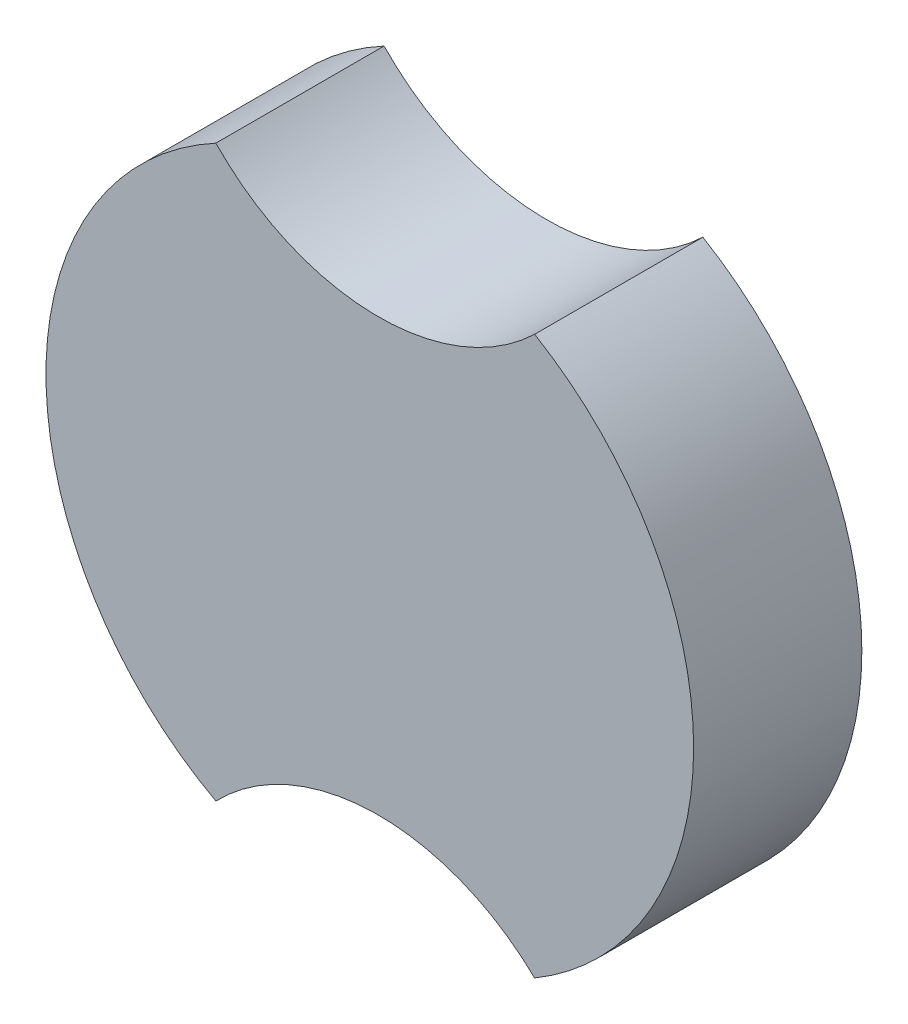
SolidWorks part; units mm, degrees
ref_plane "Спереди" through (0, 0, 0) normal (0, 0, 1) x (1, 0, 0)
ref_plane "Сверху" through (0, 0, 0) normal (0, 1, 0) x (1, 0, 0)
ref_plane "Справа" through (0, 0, 0) normal (1, 0, 0) x (0, 0, -1)
sketch "Эскиз1" plane through (0, 0, 0) normal (0, 0, 1) x (1, 0, 0)
  line L0 (-38.5, 0) -> (38.5, 0) construction
  circle A0 centre (0, 0) radius 38.5
  dimension "D1" = 77
extrude "Бобышка-Вытянуть2" add sketch "Эскиз1" along normal blind 20
sketch "Эскиз3" plane through (0, 0, 0) normal (0, 0, 1) x (1, 0, 0)
  circle A0 centre (0, 0) radius 38.5 construction
  arc A1 (-18.3013, 33.872) -> (19.5977, 33.1388) centre (1.0147, 52.4549) ccw
  arc A2 (-18.3013, -33.872) -> (19.5977, -33.1388) centre (1.0147, -52.4549) cw
  arc A3 (-18.3013, -33.872) -> (19.5977, -33.1388) centre (0, 0) ccw
  arc A4 (19.5977, 33.1388) -> (-18.3013, 33.872) centre (0, 0) ccw
extrude "Вырез-Вытянуть1" cut sketch "Эскиз3" along normal blind 20
sketch "Эскиз4" plane through (0, 0, 0) normal (0, 0, 1) x (1, 0, 0)
  circle A0 centre (0, 0) radius 2.5
extrude "Вырез-Вытянуть2" cut sketch "Эскиз4" along normal blind 8
